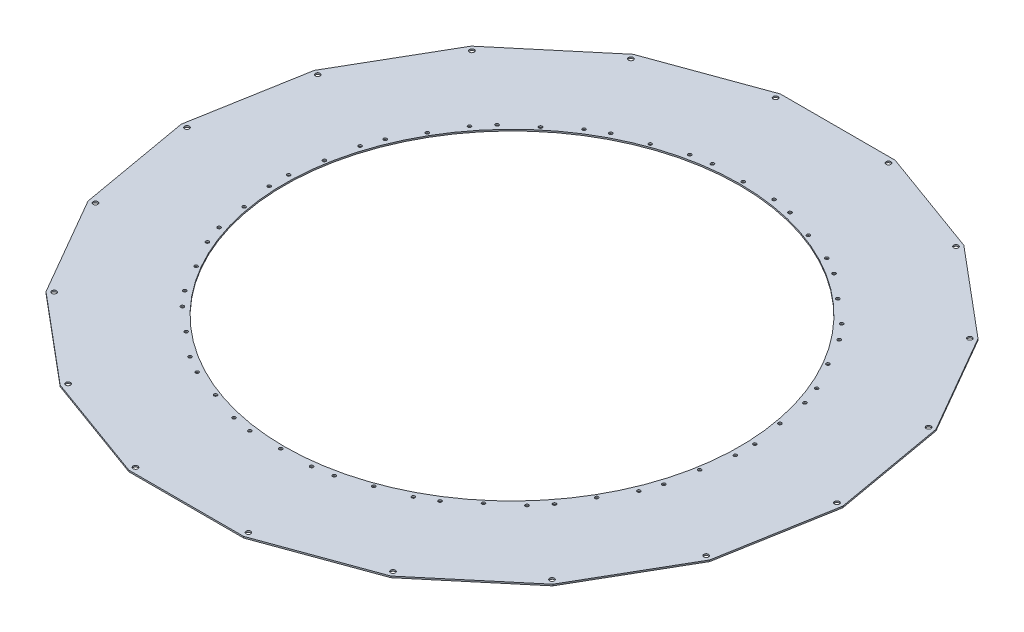
SolidWorks part; units mm, degrees
material "6061-T6 (SS)"
ref_plane "Front" through (0, 0, 0) normal (0, 0, 1) x (1, 0, 0)
ref_plane "Top" through (0, 0, 0) normal (0, 1, 0) x (1, 0, 0)
ref_plane "Right" through (0, 0, 0) normal (1, 0, 0) x (0, 0, -1)
sketch "Sketch1" plane through (0, 0, 0) normal (0, 1, 0) x (1, 0, 0)
  line L0 (0, 0) -> (-715, 0) construction
  line L1 (-715, 0) -> (-671.8802, -244.5444)
  line L2 (-671.8802, -244.5444) -> (-547.7218, -459.5931)
  line L3 (-547.7218, -459.5931) -> (-357.5, -619.2082)
  line L4 (-357.5, -619.2082) -> (-124.1584, -704.1375)
  line L5 (-124.1584, -704.1375) -> (124.1584, -704.1375)
  line L6 (124.1584, -704.1375) -> (357.5, -619.2082)
  line L7 (357.5, -619.2082) -> (547.7218, -459.5931)
  line L8 (547.7218, -459.5931) -> (671.8802, -244.5444)
  line L9 (671.8802, -244.5444) -> (715, 0)
  line L10 (715, 0) -> (671.8802, 244.5444)
  line L11 (671.8802, 244.5444) -> (547.7218, 459.5931)
  line L12 (547.7218, 459.5931) -> (357.5, 619.2082)
  line L13 (357.5, 619.2082) -> (124.1584, 704.1375)
  line L14 (124.1584, 704.1375) -> (-124.1584, 704.1375)
  line L15 (-124.1584, 704.1375) -> (-357.5, 619.2082)
  line L16 (-357.5, 619.2082) -> (-547.7218, 459.5931)
  line L17 (-547.7218, 459.5931) -> (-671.8802, 244.5444)
  line L18 (-671.8802, 244.5444) -> (-715, 0)
  circle A1 centre (0, 0) radius 492.125
  circle A2 centre (0, 0) radius 715 construction
  dimension "D2" = 984.25
  dimension "D3" = 1430
extrude "Boss-Extrude1" add sketch "Sketch1" along normal blind 3.175
hole_wizard "3/8 Clearance Hole1" positions "Sketch13" profile "Sketch14" hole size "3/8" standard "ANSI Inch" end condition through all
sketch "Sketch13" plane through (0, 3.175, 0) normal (0, 1, 0) x (1, 0, 0)
  line L0 (0, 0) -> (-121.9878, -691.8274) construction
  line L2 (0, 0) -> (0, -704.1375) construction
  line L4 (-124.1584, -704.1375) -> (124.1584, -704.1375) construction
  point P0 (-121.9878, -691.8274)
  point P16 (0, -704.1375)
  dimension "D1" = 10
  dimension "D2" = 702.5
sketch "Sketch14" plane through (-121.9878, 3.175, 691.8274) normal (1, 0, 0) x (0, 0, 1)
  line L0 (0, 0) -> (0, 3.175)
  line L1 (0, 3.175) -> (5.1587, 3.175)
  line L2 (5.1587, 3.175) -> (5.1587, 0)
  line L5 (5.1587, 0) -> (0, 0)
  line L11 (0, -6.35) -> (0, 107.95) construction
  dimension "Thru Hole Dia." = 10.3175
  dimension "Thru Hole Depth" = 3.175
hole_wizard "1/4 Clearance Hole for RFoF" positions "Sketch10" profile "Sketch11" hole size "1/4" standard "ANSI Inch" end condition through all
sketch "Sketch10" plane through (0, 3.175, 0) normal (0, 1, 0) x (1, 0, 0)
  line L0 (-66.675, -499.9053) -> (66.675, -499.9053) construction
  line L3 (0, -704.1375) -> (0, -499.9053) construction
  line L4 (-124.1584, -704.1375) -> (124.1584, -704.1375) construction
  line L5 (0, 0) -> (0, -499.9053) construction
  point P0 (-66.675, -499.9053)
  point P2 (66.675, -499.9053)
  point P15 (0, -499.9053)
  point P20 (0, -704.1375)
  dimension "D1" = 133.35
  dimension "D2" = 204.2322
  dimension "D3" = 499.9053
sketch "Sketch11" plane through (-66.675, 3.175, 499.9053) normal (1, 0, 0) x (0, 0, 1)
  line L0 (0, 0) -> (0, 3.175)
  line L1 (0, 3.175) -> (3.5712, 3.175)
  line L2 (3.5712, 3.175) -> (3.5712, 0)
  line L5 (3.5712, 0) -> (0, 0)
  line L11 (0, -6.35) -> (0, 107.95) construction
  dimension "Thru Hole Dia." = 7.1425
  dimension "Thru Hole Depth" = 3.175
pattern_circular "CirPattern - 18x Mount Holes In_Out" count 18 over 360 about axis through (0, 0, 0) along (0, 1, 0) of "1/4 Clearance Hole for RFoF", "3/8 Clearance Hole1"
